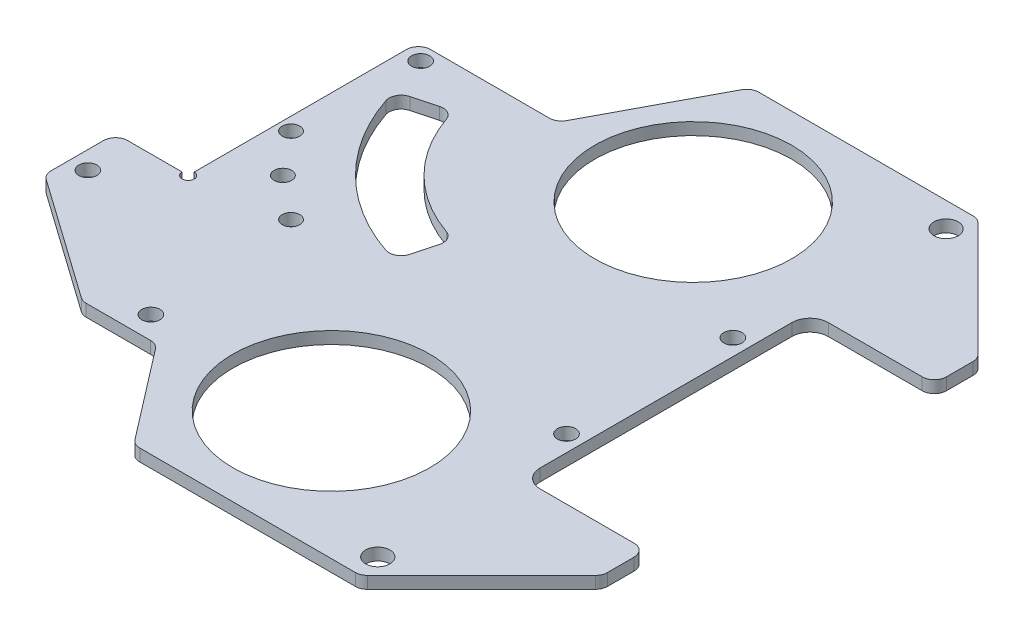
SolidWorks part; units mm, degrees
ref_plane "前视基准面" through (0, 0, 0) normal (0, 0, 1) x (1, 0, 0)
ref_plane "上视基准面" through (0, 0, 0) normal (0, 1, 0) x (1, 0, 0)
ref_plane "右视基准面" through (0, 0, 0) normal (1, 0, 0) x (0, 0, -1)
sketch "Sketch1" plane through (0, 0, 0) normal (0, 1, 0) x (1, 0, 0)
  line L0 (-12.3922, -6.9813) -> (-12.3922, -30.7587)
  line L7 (-83.2766, -26.8979) -> (-83.2766, 11.13)
  line L8 (-84.1301, -26.8979) -> (-83.2766, -26.8979)
  line L9 (-49.2817, 32.1325) -> (-11.8717, 32.1325)
  line L10 (8.1283, 12.1325) -> (-11.8717, 32.1325)
  line L11 (8.1283, 12.1325) -> (8.1283, 4.9225)
  line L12 (-11.8717, -69.8725) -> (-49.2817, -69.8725)
  line L13 (-11.8717, -69.8725) -> (8.1283, -49.8725)
  line L14 (-1032.9128, -18.87) -> (-29.1716, -18.87) construction
  line L19 (-95.2712, -26.8979) -> (-95.2712, -38.5968)
  line L20 (-61.7969, -53.5968) -> (-74.058, -53.5968)
  line L21 (-95.2712, -38.5968) -> (-74.058, -53.5968)
  line L22 (-61.7969, -53.5968) -> (-49.2817, -69.8725)
  line L23 (-95.2712, -26.8979) -> (-84.1301, -26.8979)
  line L24 (-83.2766, 11.13) -> (-60.4485, 11.13)
  line L25 (-60.4485, 11.13) -> (-49.2817, 32.1325)
  line L28 (-12.3922, 0.13) -> (-12.3922, -6.9813)
  line L29 (8.1283, 4.9225) -> (-9.3922, 4.9225)
  line L30 (-12.3922, 1.9225) -> (-12.3922, 0.13)
  line L31 (-9.3922, -42.6625) -> (8.1283, -42.6625)
  line L32 (-12.3922, -39.6625) -> (-12.3922, -37.87)
  line L33 (8.1283, -42.6625) -> (8.1283, -49.8725)
  line L34 (8.1283, -18.87) -> (19.2407, -18.87) construction
  line L37 (-52.665, -16.0067) -> (-53.7025, -19.8791)
  line L38 (-76.2857, 2.7041) -> (-72.4134, 3.7417)
  line L42 (-12.3922, -30.7587) -> (-12.3922, -37.87)
  circle A1 centre (-37.7817, -48.7475) radius 16.2647
  circle A3 centre (-37.7817, 11.0075) radius 16.2647
  circle A8 centre (-15.0871, -5.1272) radius 1.5
  circle A9 centre (-15.0871, -32.6128) radius 1.5
  arc A10 (-9.3922, 4.9225) -> (-12.3922, 1.9225) centre (-9.3922, 1.9225) ccw
  arc A11 (-9.3922, -42.6625) -> (-12.3922, -39.6625) centre (-9.3922, -39.6625) cw
  circle A12 centre (-81.1279, -12.0642) radius 1.45
  circle A13 centre (-75.4701, -19.0634) radius 1.45
  circle A14 centre (-68.4709, -24.7213) radius 1.45
  arc A20 (-52.665, -16.0067) -> (-53.9425, -13.5991) centre (-54.5968, -15.4891) ccw
  arc A21 (-56.2718, -21.2572) -> (-53.7025, -19.8791) centre (-55.6344, -19.3614) ccw
  arc A22 (-70.0058, 2.4641) -> (-53.9425, -13.5991) centre (-45.4365, 10.9701) ccw
  arc A23 (-70.0058, 2.4641) -> (-72.4134, 3.7417) centre (-71.8957, 1.8098) ccw
  arc A24 (-76.2857, 2.7041) -> (-77.6638, 0.1349) centre (-75.7681, 0.7722) ccw
  arc A25 (-77.6638, 0.1349) -> (-56.2718, -21.2572) centre (-45.4365, 10.9701) ccw
  circle A26 centre (-92.3112, -34.4379) radius 1.5
  circle A27 centre (-66.463, -49.8725) radius 1.5
  circle A29 centre (-80.4556, 8.667) radius 1.5
  point P65 (-29.1716, -9.9813)
  point P72 (-29.1716, -27.7587)
  point P75 (-12.3922, -9.9813)
  point P78 (-12.3922, -27.7587)
  dimension "D1" = 3
extrude "Boss-Extrude1" add sketch "Sketch1" along normal blind 2
sketch "Sketch2" plane through (0, 2, 0) normal (0, 1, 0) x (1, 0, 0)
  circle A1 centre (-13.0675, -65.7991) radius 2
  circle A3 centre (-13.0675, 28.0592) radius 2
extrude "Cut-Extrude1" cut sketch "Sketch2" against normal through all
fillet "Fillet1" radius 2 14 edges at (-11.8717, 1, -32.1325) (8.1283, 1, -4.9225) (8.1283, 1, -12.1325) (8.1283, 1, 49.8725) (8.1283, 1, 42.6625) (-11.8717, 1, 69.8725) (-49.2817, 1, 69.8725) (-61.7969, 1, 53.5968) (-74.058, 1, 53.5968) (-95.2712, 1, 38.5968) (-95.2712, 1, 26.8979) (-83.2766, 1, -11.13) (-60.4485, 1, -11.13) (-49.2817, 1, -32.1325)
sketch "Sketch3" plane through (0, 2, 0) normal (0, 1, 0) x (1, 0, 0)
  circle A0 centre (-83.2766, -26.8979) radius 1
extrude "Cut-Extrude2" cut sketch "Sketch3" against normal blind 10
